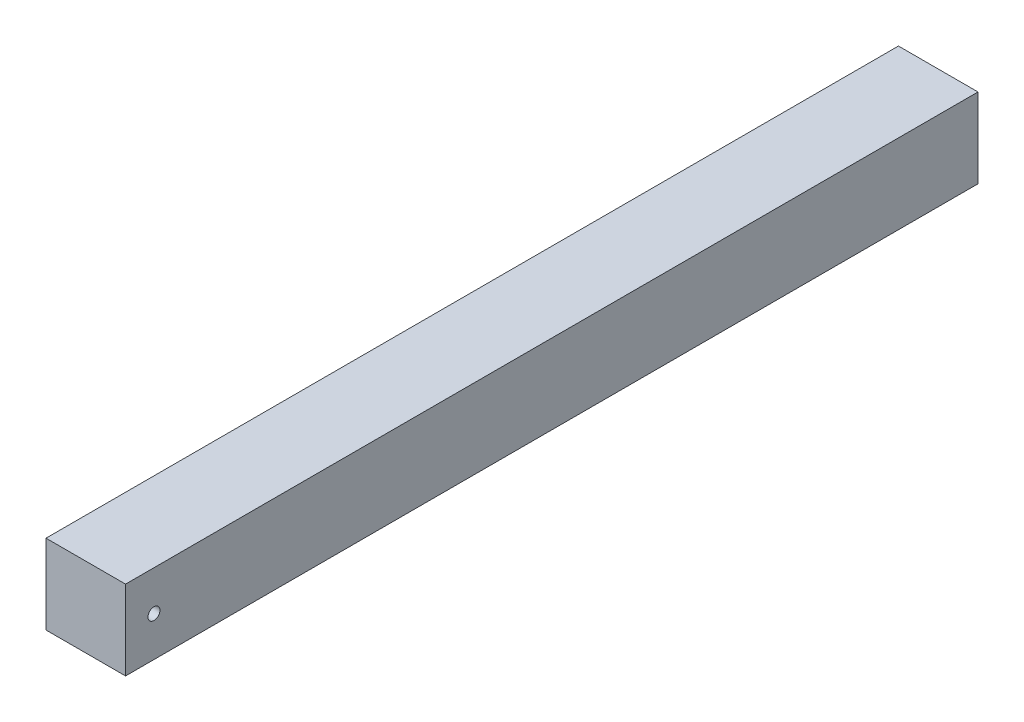
SolidWorks part; units mm, degrees
ref_plane "正面" through (0, 0, 0) normal (0, 0, 1) x (1, 0, 0)
ref_plane "平面" through (0, 0, 0) normal (0, 1, 0) x (1, 0, 0)
ref_plane "右側面" through (0, 0, 0) normal (1, 0, 0) x (0, 0, -1)
sketch "ｽｹｯﾁ1" plane through (0, 0, 0) normal (0, 0, 1) x (1, 0, 0)
  line L1 (-7, 7) -> (7, 7)
  line L2 (-7, 7) -> (-7, -7)
  line L3 (-7, -7) -> (7, -7)
  line L4 (7, 7) -> (7, -7)
  line L5 (-7, 7) -> (7, -7) construction
  line L6 (-7, -7) -> (7, 7) construction
  point P0 (0, 0)
  dimension "D1" = 14
  dimension "D2" = 14
extrude "ﾎﾞｽ - 押し出し1" add sketch "ｽｹｯﾁ1" along normal blind 150
sketch "ｽｹｯﾁ2" plane through (0, 0, 0) normal (1, 0, 0) x (0, 0, -1)
  line L0 (-150, -7) -> (-150, 7) construction
  circle A0 centre (-145, 0) radius 1.05
  dimension "D1" = 2.1
  dimension "D2" = 5
extrude "ｶｯﾄ - 押し出し1" cut sketch "ｽｹｯﾁ2" against normal through all both and the other way through all
